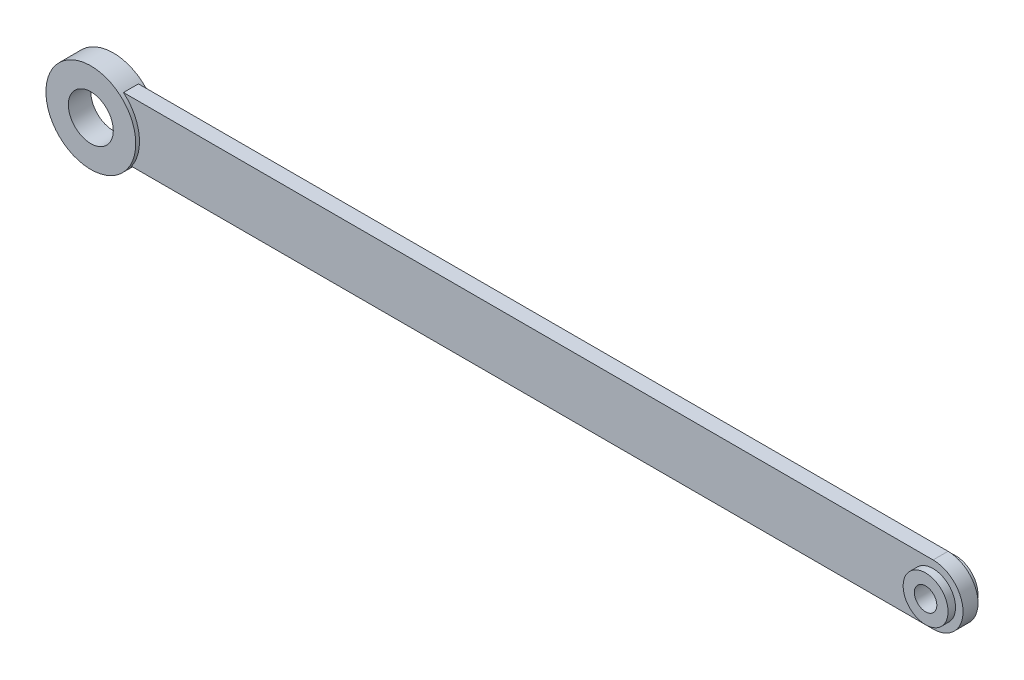
SolidWorks part; units mm, degrees
ref_plane "Front Plane" through (0, 0, 0) normal (0, 0, 1) x (1, 0, 0)
ref_plane "Top Plane" through (0, 0, 0) normal (0, 1, 0) x (1, 0, 0)
ref_plane "Right Plane" through (0, 0, 0) normal (1, 0, 0) x (0, 0, -1)
sketch "Sketch2" plane through (0, 0, 0) normal (0, 0, 1) x (1, 0, 0)
  circle A0 centre (0, 0) radius 3000
  circle A1 centre (0, 0) radius 6000
  dimension "D1" = 6000
  dimension "D2" = 12000
extrude "Boss-Extrude1" add sketch "Sketch2" along normal blind 3000
ref_plane "Plane2" through (0, 0, 1500) normal (0, 0, 1) x (1, 0, 0)
sketch "Sketch3" plane through (0, 0, 1500) normal (0, 0, 1) x (1, 0, 0)
  line L1 (1140.415, 4594.3074) -> (112000, 4594.3074)
  line L3 (3287.7751, -3405.6926) -> (112000, -3405.6926)
  arc A1 (112000, -3405.6926) -> (112000, 4594.3074) centre (112000, 594.3074) ccw
  arc A2 (3287.7751, -3405.6926) -> (1140.415, 4594.3074) centre (0, 0) ccw
  dimension "D1" = 8000
extrude "Boss-Extrude2" add sketch "Sketch3" along normal blind 1000 and the other way blind 1000
sketch "Sketch4" plane through (0, 0, 500) normal (0, 0, -1) x (-1, 0, 0)
  circle A0 centre (-112000, 594.3074) radius 3000
extrude "Boss-Extrude3" add sketch "Sketch4" along normal blind 1000 and the other way blind 3000
sketch "Sketch5" plane through (0, 0, -500) normal (0, 0, -1) x (-1, 0, 0)
  circle A0 centre (-112000, 594.3074) radius 1500
extrude "Cut-Extrude1" cut sketch "Sketch5" against normal blind 5000
scale "Scale1" scale about centroid uniform scaling yes scale factor 0.001
sketch "Sketch8" plane through (0, 0, 1501.5) normal (0, 0, 1) x (1, 0, 0)
  point P0 (53443.6657, 524.4918)
